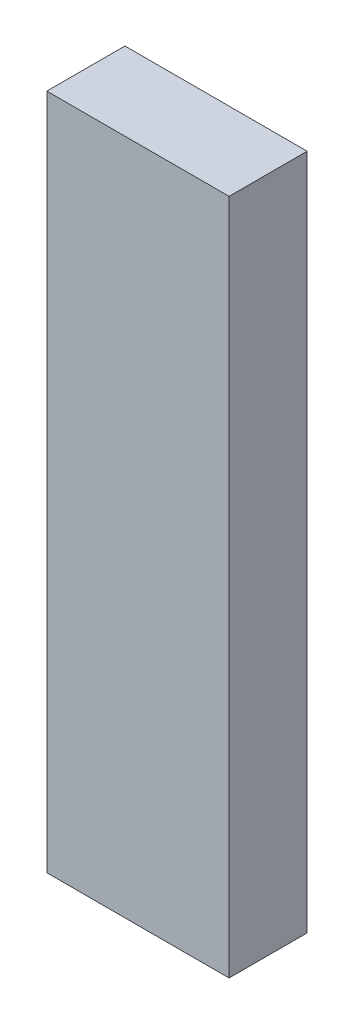
SolidWorks part; units mm, degrees
material "Pine"
ref_plane "Front Plane" through (0, 0, 0) normal (0, 0, 1) x (1, 0, 0)
ref_plane "Top Plane" through (0, 0, 0) normal (0, 1, 0) x (1, 0, 0)
ref_plane "Right Plane" through (0, 0, 0) normal (1, 0, 0) x (0, 0, -1)
sketch "Sketch1" plane through (0, 0, 0) normal (0, 1, 0) x (1, 0, 0)
  line L1 (0, 0) -> (88.9, 0)
  line L2 (0, 0) -> (0, 38.1)
  line L3 (0, 38.1) -> (88.9, 38.1)
  line L4 (88.9, 0) -> (88.9, 38.1)
  dimension "D1" = 88.9
  dimension "D2" = 38.1
extrude "Boss-Extrude1" add sketch "Sketch1" along normal up to surface (330.2 mm away)
